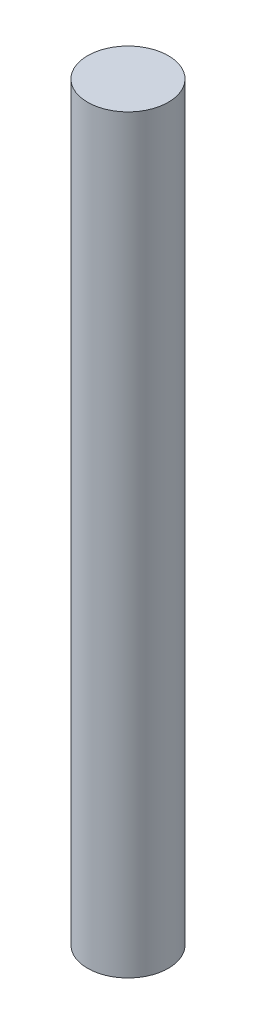
SolidWorks part; units mm, degrees
ref_plane "Alzado" through (0, 0, 0) normal (0, 0, 1) x (1, 0, 0)
ref_plane "Planta" through (0, 0, 0) normal (0, 1, 0) x (1, 0, 0)
ref_plane "Vista lateral" through (0, 0, 0) normal (1, 0, 0) x (0, 0, -1)
sketch "Croquis1" plane through (0, 0, 0) normal (0, 1, 0) x (1, 0, 0)
  circle A0 centre (0, 0) radius 53.8173
extrude "Saliente-Extruir1" add sketch "Croquis1" along normal blind 1000
